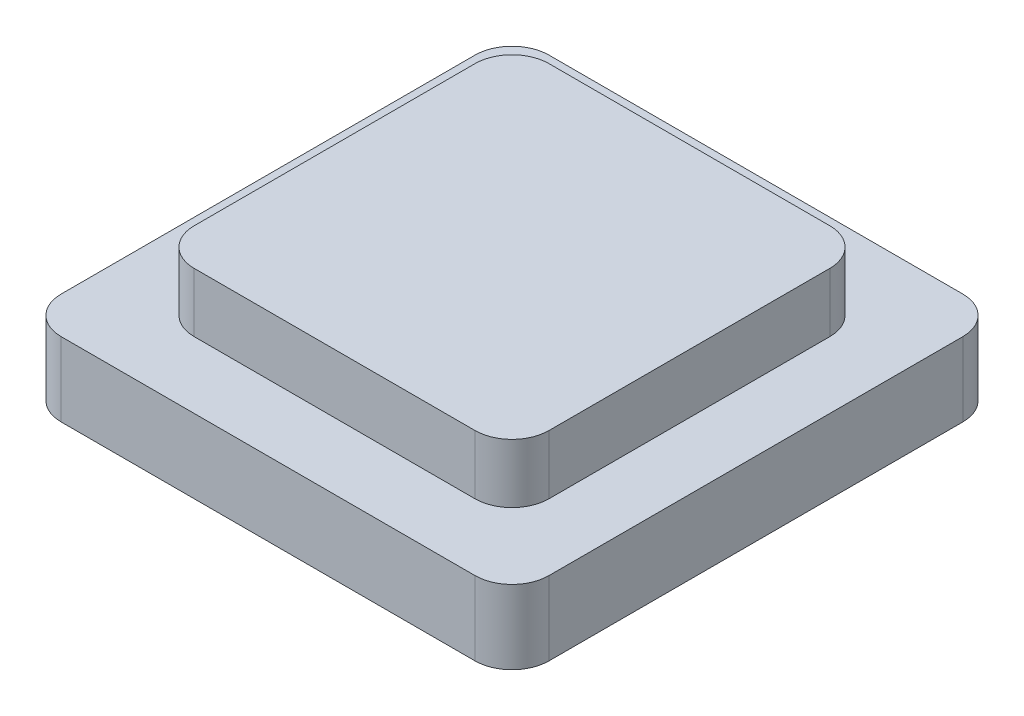
SolidWorks part; units mm, degrees
ref_plane "前视基准面" through (0, 0, 0) normal (0, 0, 1) x (1, 0, 0)
ref_plane "上视基准面" through (0, 0, 0) normal (0, 1, 0) x (1, 0, 0)
ref_plane "右视基准面" through (0, 0, 0) normal (1, 0, 0) x (0, 0, -1)
other "Configuration Table"
sketch "草图1" plane through (0, 0, 0) normal (0, 1, 0) x (1, 0, 0)
  line L1 (-3.8, 4.8) -> (3.8, 4.8)
  line L2 (-4.8, 3.8) -> (-4.8, -3.8)
  line L3 (-3.8, -4.8) -> (3.8, -4.8)
  line L4 (4.8, 3.8) -> (4.8, -3.8)
  line L5 (-4.8, 4.8) -> (4.8, -4.8) construction
  line L6 (-4.8, -4.8) -> (4.8, 4.8) construction
  arc A0 (-4.8, -3.8) -> (-3.8, -4.8) centre (-3.8, -3.8) ccw
  arc A1 (3.8, -4.8) -> (4.8, -3.8) centre (3.8, -3.8) ccw
  arc A2 (3.8, 4.8) -> (4.8, 3.8) centre (3.8, 3.8) cw
  arc A3 (-3.8, 4.8) -> (-4.8, 3.8) centre (-3.8, 3.8) ccw
  point P0 (0, 0)
  dimension "D3" = 1
  dimension "D1" = 9.6
  dimension "D2" = 9.6
extrude "凸台-拉伸1" add sketch "草图1" along normal blind 1.6
sketch "草图2" plane through (0, 0, 0) normal (0, -1, 0) x (1, 0, 0)
  line L1 (-5.6, 6.6) -> (5.6, 6.6)
  line L2 (-6.6, 5.6) -> (-6.6, -5.6)
  line L3 (-5.6, -6.6) -> (5.6, -6.6)
  line L4 (6.6, 5.6) -> (6.6, -5.6)
  line L5 (-6.6, 6.6) -> (6.6, -6.6) construction
  line L6 (-6.6, -6.6) -> (6.6, 6.6) construction
  arc A0 (-6.6, -5.6) -> (-5.6, -6.6) centre (-5.6, -5.6) ccw
  arc A1 (5.6, -6.6) -> (6.6, -5.6) centre (5.6, -5.6) ccw
  arc A2 (5.6, 6.6) -> (6.6, 5.6) centre (5.6, 5.6) cw
  arc A3 (-5.6, 6.6) -> (-6.6, 5.6) centre (-5.6, 5.6) ccw
  point P0 (0, 0)
  dimension "D3" = 1
  dimension "D1" = 13.2
  dimension "D2" = 13.2
extrude "凸台-拉伸2" add sketch "草图2" along normal blind 2
sketch "草图3" plane through (0, -2, 0) normal (0, -1, 0) x (1, 0, 0)
  line L1 (-3.3, -4.3) -> (3.3, -4.3)
  line L2 (-4.3, -3.3) -> (-4.3, 3.3)
  line L3 (-3.3, 4.3) -> (3.3, 4.3)
  line L4 (4.3, -3.3) -> (4.3, 3.3)
  line L5 (-4.3, -4.3) -> (4.3, 4.3) construction
  line L6 (-4.3, 4.3) -> (4.3, -4.3) construction
  arc A0 (3.3, 4.3) -> (4.3, 3.3) centre (3.3, 3.3) cw
  arc A1 (3.3, -4.3) -> (4.3, -3.3) centre (3.3, -3.3) ccw
  arc A2 (-3.3, -4.3) -> (-4.3, -3.3) centre (-3.3, -3.3) cw
  arc A3 (-4.3, 3.3) -> (-3.3, 4.3) centre (-3.3, 3.3) cw
  point P0 (0, 0)
  dimension "D3" = 1
  dimension "D1" = 8.6
  dimension "D2" = 8.6
extrude "切除-拉伸1" cut sketch "草图3" against normal offset from surface (3.1 mm away) 0.5 up to face at (0, 1.6, 0)
sketch "草图4" plane through (0, -2, 0) normal (0, -1, 0) x (1, 0, 0)
  line L0 (5.6, 6.6) -> (-5.6, 6.6) construction
  line L1 (-4.6, 5.6) -> (4.6, 5.6)
  line L2 (-5.6, 4.6) -> (-5.6, -4.6)
  line L3 (-4.6, -5.6) -> (4.6, -5.6)
  line L4 (5.6, 4.6) -> (5.6, -4.6)
  line L5 (-5.6, 5.6) -> (5.6, -5.6) construction
  line L6 (-5.6, -5.6) -> (5.6, 5.6) construction
  line L7 (6.6, -5.6) -> (6.6, 5.6) construction
  arc A0 (-5.6, -4.6) -> (-4.6, -5.6) centre (-4.6, -4.6) ccw
  arc A1 (4.6, -5.6) -> (5.6, -4.6) centre (4.6, -4.6) ccw
  arc A2 (4.6, 5.6) -> (5.6, 4.6) centre (4.6, 4.6) cw
  arc A3 (-4.6, 5.6) -> (-5.6, 4.6) centre (-4.6, 4.6) ccw
  point P0 (0, 0)
  dimension "D3" = 1
  dimension "D1" = 1
  dimension "D2" = 1
extrude "切除-拉伸2" cut sketch "草图4" against normal blind 1
